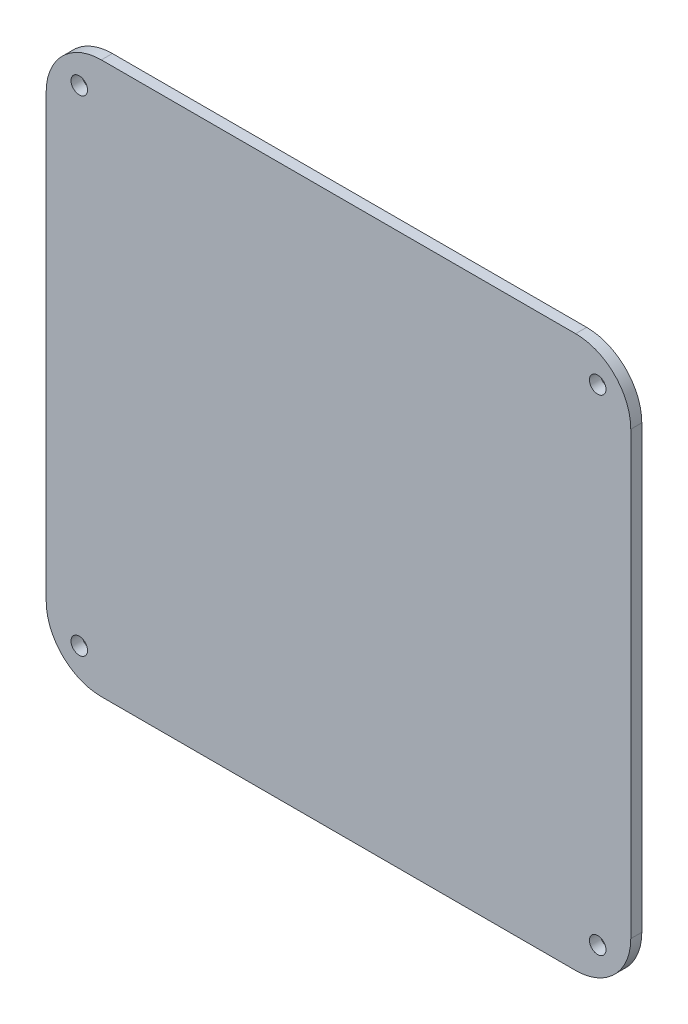
SolidWorks part; units mm, degrees
ref_plane "Front Plane" through (0, 0, 0) normal (0, 0, 1) x (1, 0, 0)
ref_plane "Top Plane" through (0, 0, 0) normal (0, 1, 0) x (1, 0, 0)
ref_plane "Right Plane" through (0, 0, 0) normal (1, 0, 0) x (0, 0, -1)
sketch "Sketch1" plane through (0, 0, 0) normal (0, 0, 1) x (1, 0, 0)
  line L4 (-43, 260) -> (43, 260)
  line L5 (53, 270) -> (53, 350)
  line L6 (43, 360) -> (-43, 360)
  line L7 (-53, 350) -> (-53, 270)
  arc A4 (43, 260) -> (53, 270) centre (43, 270) ccw
  arc A5 (53, 350) -> (43, 360) centre (43, 350) ccw
  arc A6 (-43, 360) -> (-53, 350) centre (-43, 350) ccw
  arc A7 (-53, 270) -> (-43, 260) centre (-43, 270) ccw
extrude "Boss-Extrude1" add sketch "Sketch1" against normal blind 2
sketch "Sketch2" plane through (0, 0, -2) normal (0, 0, -1) x (-1, 0, 0)
  circle A1 centre (47, 266) radius 1.5
  circle A3 centre (47, 354) radius 1.5
  circle A5 centre (-47, 354) radius 1.5
  circle A7 centre (-47, 266) radius 1.5
extrude "Cut-Extrude1" cut sketch "Sketch2" against normal blind 3
